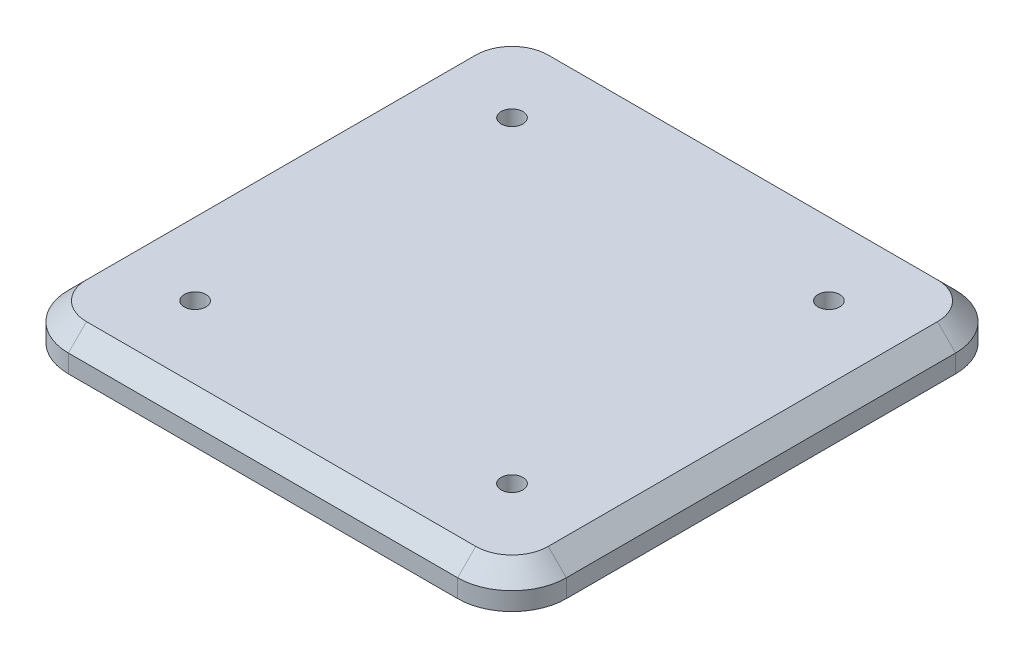
SolidWorks part; units mm, degrees
ref_plane "前基準面" through (0, 0, 0) normal (0, 0, 1) x (1, 0, 0)
ref_plane "上基準面" through (0, 0, 0) normal (0, 1, 0) x (1, 0, 0)
ref_plane "右基準面" through (0, 0, 0) normal (1, 0, 0) x (0, 0, -1)
sketch "草圖1" plane through (0, 0, 0) normal (0, 1, 0) x (1, 0, 0)
  line L1 (0, 0) -> (275, 0)
  line L2 (0, 0) -> (0, 275)
  line L3 (0, 275) -> (275, 275)
  line L4 (275, 0) -> (275, 275)
  dimension "D1" = 275
  dimension "D2" = 275
extrude "填料-伸長1" add sketch "草圖1" along normal blind 20
fillet "圓角1" radius 30 4 edges at (0, 10, -275) (275, 10, -275) (275, 10, 0) (0, 10, 0)
chamfer "導角1" distance 10 angle 45 8 edges at (0, 20, -137.5) (8.7868, 20, -8.7868) (8.7868, 20, -266.2132) (137.5, 20, 0) (137.5, 20, -275) (266.2132, 20, -8.7868) (266.2132, 20, -266.2132) (275, 20, -137.5)
sketch "草圖2" plane through (0, 0, 0) normal (0, -1, 0) x (1, 0, 0)
  line L0 (30, 0) -> (245, 0) construction
  line L1 (25, -25) -> (250, -25)
  line L2 (25, -25) -> (25, -250)
  line L3 (25, -250) -> (250, -250)
  line L4 (250, -25) -> (250, -250)
  line L5 (245, -275) -> (30, -275) construction
  line L6 (275, -30) -> (275, -245) construction
  line L7 (0, -245) -> (0, -30) construction
  dimension "D1" = 25
  dimension "D2" = 25
  dimension "D3" = 25
  dimension "D4" = 25
sketch "草圖4" plane through (0, 20, 0) normal (0, 1, 0) x (1, 0, 0)
  line L0 (25, 25) -> (25, 250) construction
  line L1 (50, 50) -> (225, 50)
  line L2 (50, 50) -> (50, 225)
  line L3 (50, 225) -> (225, 225)
  line L4 (225, 50) -> (225, 225)
  line L5 (25, 25) -> (250, 25) construction
  line L6 (250, 25) -> (250, 250) construction
  line L7 (25, 250) -> (250, 250) construction
  dimension "D1" = 25
  dimension "D2" = 25
  dimension "D3" = 25
  dimension "D4" = 25
hole_wizard "Ø20.0mm 定位孔1" positions "3D草圖2" profile "草圖6" hole size "Ø20.0" standard "ISO"
sketch3d "3D草圖2"
  point P0 (50, 20, -50)
  point P3 (50, 20, -225)
  point P6 (225, 20, -225)
  point P9 (225, 20, -50)
  point P12 (25, 0, -25)
  point P15 (250, 0, -25)
  point P18 (250, 0, -250)
  point P25 (25, 0, -250)
sketch "草圖6" plane through (50, 20, -50) normal (1, 0, 0) x (0, 0, 1)
  line L0 (0, 0) -> (0, 13.6052)
  line L1 (0, 13.6052) -> (6, 10)
  line L2 (6, 10) -> (6, 0)
  line L5 (6, 0) -> (0, 0)
  line L10 (0, 13.6052) -> (-6, 10) construction
  line L11 (0, -6.35) -> (0, 107.95) construction
  dimension "鑽孔直徑" = 12
  dimension "鑽孔深度" = 10
  dimension "導頭角度" = 118
